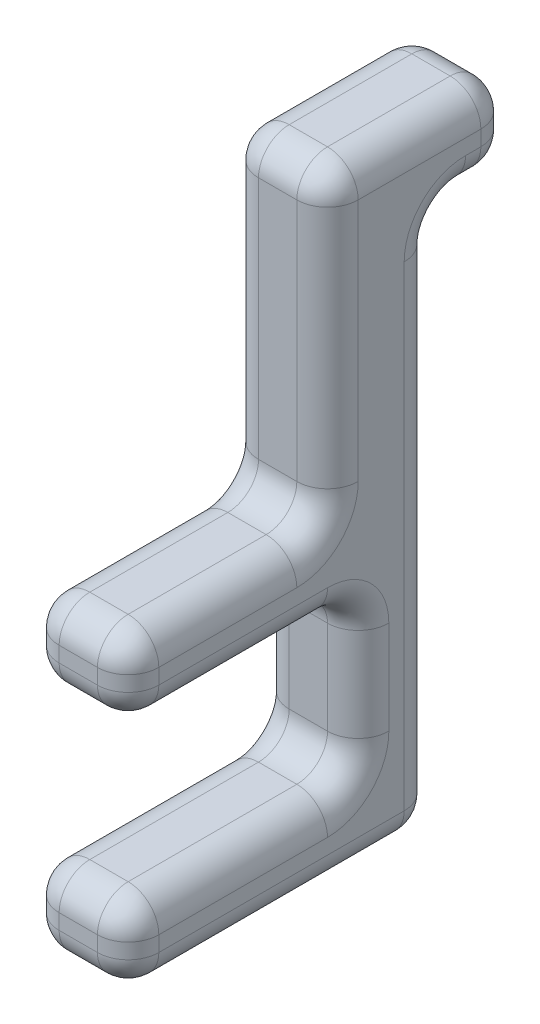
SolidWorks part; units mm, degrees
ref_plane "Front Plane" through (0, 0, 0) normal (0, 0, 1) x (1, 0, 0)
ref_plane "Top Plane" through (0, 0, 0) normal (0, 1, 0) x (1, 0, 0)
ref_plane "Right Plane" through (0, 0, 0) normal (1, 0, 0) x (0, 0, -1)
sketch "Sketch1" plane through (0, 0, 0) normal (0, 0, 1) x (1, 0, 0)
  line L1 (0, 0) -> (-6.5, 0)
  line L2 (0, 0) -> (0, 40)
  line L3 (0, 40) -> (-6.5, 40)
  line L4 (-6.5, 0) -> (-6.5, 40)
  dimension "D1" = 40
  dimension "D2" = 6.5
extrude "Boss-Extrude1" add sketch "Sketch1" along normal blind 20
sketch "Sketch2" plane through (0, 0, 0) normal (1, 0, 0) x (0, 0, -1)
  line L0 (-20, 0) -> (-20, 40) construction
  line L1 (-20, 15.1) -> (-5, 15.1)
  line L2 (-20, 15.1) -> (-20, 5)
  line L3 (-20, 5) -> (-5, 5)
  line L4 (-5, 15.1) -> (-5, 5)
  line L5 (-20, 0) -> (0, 0) construction
  line L6 (0, 0) -> (0, 40) construction
  dimension "D1" = 5
  dimension "D2" = 5
  dimension "10,5" = 10.1
extrude "Cut-Extrude1" cut sketch "Sketch2" against normal through all
fillet "Fillet1" radius 2 8 edges at (-6.5, 5, 12.5) (0, 5, 12.5) (-6.5, 15.1, 12.5) (0, 15.1, 12.5) (-3.25, 5, 5) (-6.5, 10.05, 5) (-3.25, 15.1, 5) (0, 10.05, 5)
sketch "Sketch4" plane through (-6.5, 0, 0) normal (-1, 0, 0) x (0, 0, 1)
  line L1 (20, 20.1) -> (7, 20.1)
  line L2 (20, 20.1) -> (20, 40)
  line L3 (20, 40) -> (7, 40)
  line L4 (7, 20.1) -> (7, 40)
  line L12 (20, 15.1) -> (7, 15.1) construction
  dimension "D1" = 5
extrude "Cut-Extrude3" cut sketch "Sketch4" against normal through all
sketch "Sketch6" plane through (0, 0, 0) normal (0, 0, -1) x (-1, 0, 0)
  line L1 (0, 40) -> (6.5, 40)
  line L2 (0, 40) -> (0, 35)
  line L3 (0, 35) -> (6.5, 35)
  line L4 (6.5, 40) -> (6.5, 35)
  dimension "D1" = 5
extrude "Boss-Extrude2" add sketch "Sketch6" along normal blind 5
fillet "Fillet2" radius 2 32 edges at (-3.25, 35, -5) (-3.25, 40, -5) (-6.5, 35, -2.5) (-6.5, 37.5, -5) (-6.5, 40, 1) (-6.5, 17.5, 0) (-3.25, 35, 0) (-6.5, 0, 10) (-3.25, 0, 0) (-0.5858, 4.4142, 20) (-3.25, 0, 20) (-6.5, 1.5, 20) (-5.9142, 4.4142, 20) (-3.25, 5, 20) (-0.5858, 15.6858, 20) (-3.25, 15.1, 20) (-5.9142, 15.6858, 20) (-6.5, 18.6, 20) (-3.25, 20.1, 20) (-6.5, 20.1, 13.5) (-3.25, 40, 7) (-3.25, 20.1, 7) (-6.5, 30.05, 7) (0, 40, 1) (0, 37.5, -5) (0, 35, -2.5) (0, 17.5, 0) (0, 0, 10) (0, 1.5, 20) (0, 18.6, 20) (0, 20.1, 13.5) (0, 30.05, 7)
